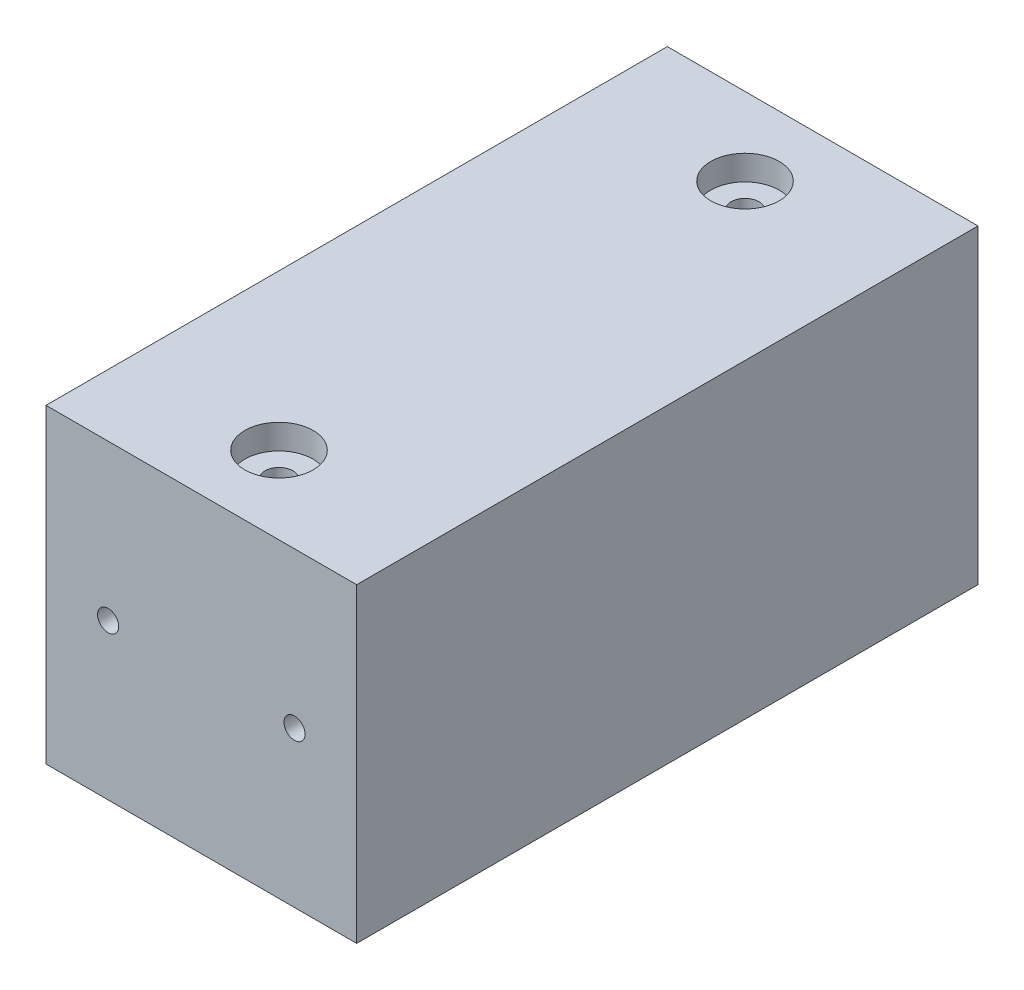
SolidWorks part; units mm, degrees
ref_plane "Ebene vorne" through (0, 0, 0) normal (0, 0, 1) x (1, 0, 0)
ref_plane "Ebene oben" through (0, 0, 0) normal (0, 1, 0) x (1, 0, 0)
ref_plane "Ebene rechts" through (0, 0, 0) normal (1, 0, 0) x (0, 0, -1)
sketch "Skizze1" plane through (0, 0, 0) normal (0, 0, 1) x (1, 0, 0)
  line L1 (50, -50) -> (-50, -50)
  line L2 (50, -50) -> (50, 50)
  line L3 (50, 50) -> (-50, 50)
  line L4 (-50, -50) -> (-50, 50)
  line L5 (50, -50) -> (-50, 50) construction
  line L6 (50, 50) -> (-50, -50) construction
  point P0 (0, 0)
  dimension "D1" = 100
extrude "Aufsatz-Linear austragen1" add sketch "Skizze1" along normal blind 200
hole_wizard "Stirnsenkung für M8 Senkschraube (Kopf Button)1" positions "Skizze3" profile "Skizze2" counterbore size "M8" standard "ANSI Metrisch" end condition through all
sketch "Skizze3" plane through (0, 50, 0) normal (0, 1, 0) x (1, 0, 0)
  line L0 (-50, -200) -> (-50, 0) construction
  line L1 (50, -200) -> (-50, -200) construction
  point P0 (0, -175)
  dimension "D1" = 50
  dimension "D2" = 25
sketch "Skizze2" plane through (0, 50, 175) normal (1, 0, 0) x (0, 0, 1)
  line L0 (0, 0) -> (0, 100)
  line L1 (0, 100) -> (4.5, 100)
  line L3 (4.5, 100) -> (4.5, 8)
  line L4 (4.5, 8) -> (11, 8)
  line L5 (11, 8) -> (11, 0)
  line L7 (11, 0) -> (0, 0)
  line L11 (0, -6.35) -> (0, 107.95) construction
  dimension "Bohrerdurchmesser" = 9
  dimension "Bohrungstiefe" = 100
  dimension "Senkdurchmesser2" = 22
  dimension "Senktiefe2" = 8
ref_plane "Ebene1" through (0, 0, 100) normal (0, 0, 1) x (1, 0, 0)
mirror "Spiegeln1" about plane through (0, 0, 100) normal (0, 0, 1) of "Stirnsenkung für M8 Senkschraube (Kopf Button)1"
hole_wizard "Kernloch für M8x1.252" positions "Skizze5" profile "Skizze4" hole size "M8x1.25" standard "ANSI Metrisch"
sketch "Skizze5" plane through (0, 0, 0) normal (0, 0, -1) x (-1, 0, 0)
  point P0 (-30, 0)
  point P3 (30, 0)
  point P6 (-30, 0)
cosmetic thread "Gewindedarstellung11" parameters "D1"=25, "D2"=8
cosmetic thread "Gewindedarstellung12" parameters "D1"=25, "D2"=8
sketch "Skizze4" plane through (30, 0, 0) normal (1, 0, 0) x (0, 1, 0)
  line L0 (0, 0) -> (0, 32.0429)
  line L1 (0, 32.0429) -> (3.4, 30)
  line L2 (3.4, 30) -> (3.4, 0)
  line L5 (3.4, 0) -> (0, 0)
  line L10 (0, 32.0429) -> (-3.4, 30) construction
  line L11 (0, -6.35) -> (0, 107.95) construction
  dimension "Bohrerdurchmesser" = 6.8
  dimension "Bohrungstiefe" = 30
  dimension "Spitzenwinkel" = 118
hole_wizard "Kernloch für M81" positions "Skizze7" profile "Skizze6" hole size "M8" standard "DIN"
sketch "Skizze7" plane through (0, 0, 200) normal (0, 0, 1) x (1, 0, 0)
  point P0 (30, 0)
  point P3 (-30, 0)
sketch "Skizze6" plane through (30, 0, 200) normal (1, 0, 0) x (0, -1, 0)
  line L0 (0, 0) -> (0, 32.0429)
  line L1 (0, 32.0429) -> (3.4, 30)
  line L2 (3.4, 30) -> (3.4, 0)
  line L5 (3.4, 0) -> (0, 0)
  line L10 (0, 32.0429) -> (-3.4, 30) construction
  line L11 (0, -6.35) -> (0, 107.95) construction
  dimension "Bohrerdurchmesser" = 6.8
  dimension "Bohrungstiefe" = 30
  dimension "Spitzenwinkel" = 118
cosmetic thread "Gewindedarstellung9" parameters "D1"=25, "D2"=8
cosmetic thread "Gewindedarstellung10" parameters "D1"=25, "D2"=8
hole_wizard "Stirnsenkung für M8 Senkschraube (Kopf Button)2" positions "Skizze9" profile "Skizze8" counterbore size "M8" standard "ANSI Metrisch" end condition through all
sketch "Skizze9" plane through (0, -50, 0) normal (0, -1, 0) x (-1, 0, 0)
  point P0 (0, -175)
  point P3 (0, -25)
sketch "Skizze8" plane through (0, -50, 175) normal (1, 0, 0) x (0, 0, -1)
  line L0 (0, 0) -> (0, 100)
  line L1 (0, 100) -> (4.5, 100)
  line L3 (4.5, 100) -> (4.5, 8)
  line L4 (4.5, 8) -> (7.5, 8)
  line L5 (7.5, 8) -> (7.5, 0)
  line L7 (7.5, 0) -> (0, 0)
  line L11 (0, -6.35) -> (0, 107.95) construction
  dimension "Bohrerdurchmesser" = 9
  dimension "Bohrungstiefe" = 100
  dimension "Senkdurchmesser2" = 15
  dimension "Senktiefe2" = 8
